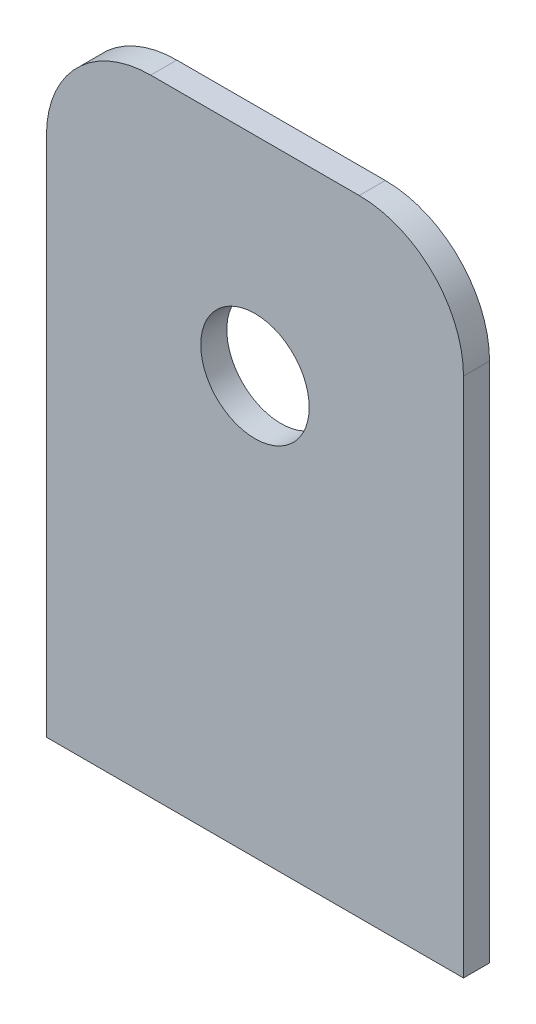
SolidWorks part; units mm, degrees
material "AISI 4130 Steel, annealed at 865C"
ref_plane "Front Plane" through (0, 0, 0) normal (0, 0, 1) x (1, 0, 0)
ref_plane "Top Plane" through (0, 0, 0) normal (0, 1, 0) x (1, 0, 0)
ref_plane "Right Plane" through (0, 0, 0) normal (1, 0, 0) x (0, 0, -1)
sketch "Sketch1" plane through (0, 0, 0) normal (0, 0, 1) x (1, 0, 0)
  line L1 (-12.7, 0) -> (12.7, 0)
  line L2 (-12.7, 0) -> (-12.7, 38.1)
  line L3 (-12.7, 38.1) -> (12.7, 38.1)
  line L4 (12.7, 0) -> (12.7, 38.1)
  line L5 (0, 38.1) -> (0, 0) construction
  line L6 (-12.7, 19.05) -> (12.7, 19.05) construction
  point P248 (0, 19.05)
  dimension "D1" = 25.4
  dimension "D2" = 38.1
extrude "Boss-Extrude1" add sketch "Sketch1" along normal blind 1.5875
sketch "Sketch2" plane through (0, 0, 1.5875) normal (0, 0, 1) x (1, 0, 0)
  line L0 (0, 0) -> (0, 25.4) construction
  line L1 (-12.7, 0) -> (12.7, 0) construction
  circle A0 centre (0, 25.4) radius 3.302
  dimension "D2" = 6.604
  dimension "D1" = 25.4
extrude "Cut-Extrude1" cut sketch "Sketch2" against normal through all both and the other way through all
fillet "Fillet1" radius 6.35 2 edges at (12.7, 38.1, 0.7937) (-12.7, 38.1, 0.7937)
